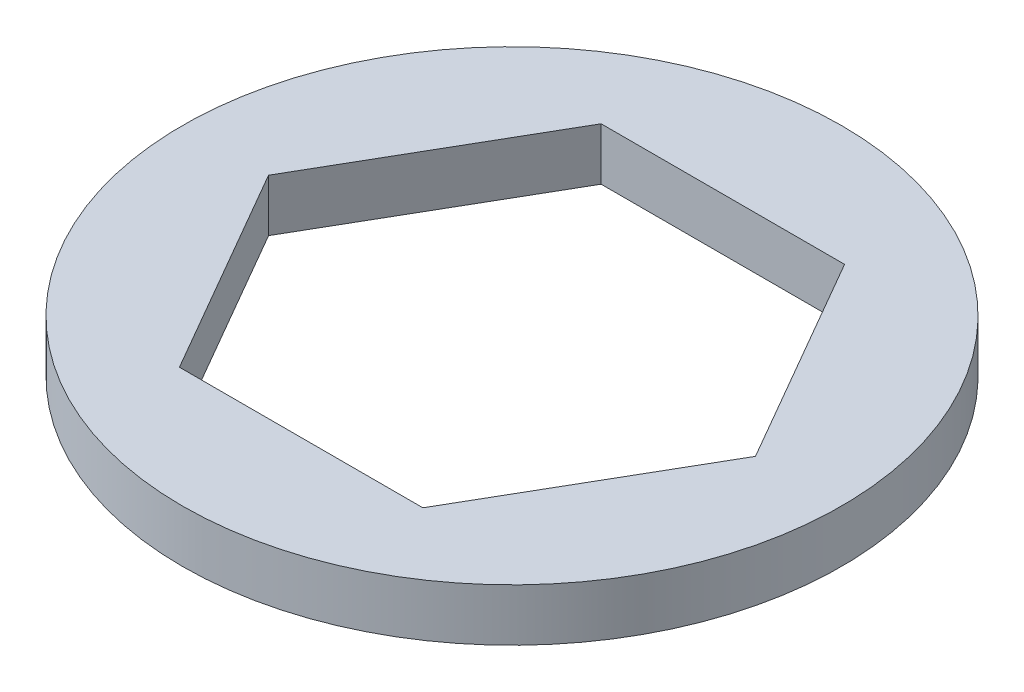
SolidWorks part; units mm, degrees
ref_plane "Front Plane" through (0, 0, 0) normal (0, 0, 1) x (1, 0, 0)
ref_plane "Top Plane" through (0, 0, 0) normal (0, 1, 0) x (1, 0, 0)
ref_plane "Right Plane" through (0, 0, 0) normal (1, 0, 0) x (0, 0, -1)
sketch "Sketch1" plane through (0, 0, 0) normal (0, 1, 0) x (1, 0, 0)
  line L1 (7.3837, 0) -> (3.6918, 6.3944)
  line L2 (3.6918, 6.3944) -> (-3.6918, 6.3944)
  line L3 (-3.6918, 6.3944) -> (-7.3837, 0)
  line L4 (-7.3837, 0) -> (-3.6918, -6.3945)
  line L5 (-3.6918, -6.3945) -> (3.6918, -6.3944)
  line L6 (3.6918, -6.3944) -> (7.3837, 0)
  circle A0 centre (0, 0) radius 6.3944 construction
  circle A1 centre (0, 0) radius 9.9949
  dimension "D1" = 12.7889
  dimension "D2" = 19.9898
extrude "Boss-Extrude1" add sketch "Sketch1" along normal blind 1.5875
